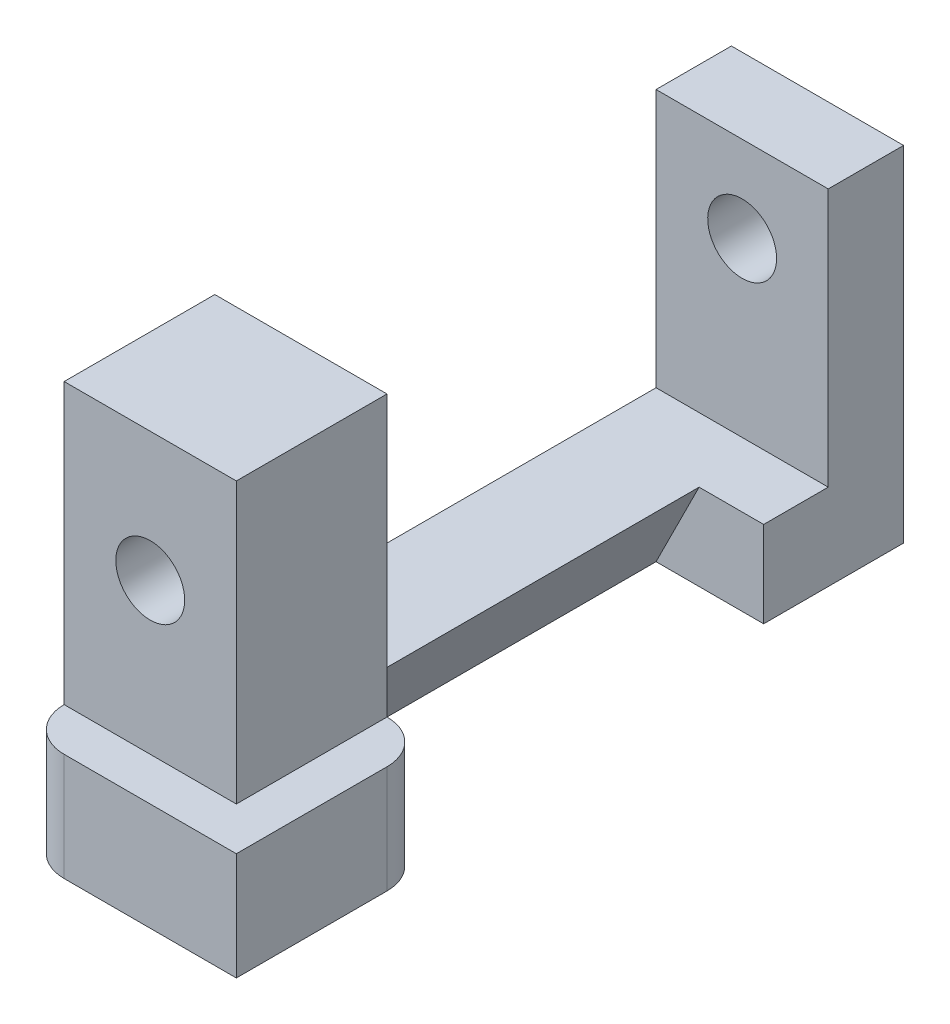
SolidWorks part; units mm, degrees
ref_plane "Front Plane" through (0, 0, 0) normal (0, 0, 1) x (1, 0, 0)
ref_plane "Top Plane" through (0, 0, 0) normal (0, 1, 0) x (1, 0, 0)
ref_plane "Right Plane" through (0, 0, 0) normal (1, 0, 0) x (0, 0, -1)
sketch "Sketch1" plane through (0, 0, 0) normal (1, 0, 0) x (0, 0, -1)
  line L0 (0, 0) -> (0, 16)
  line L1 (0, 16) -> (-3.5, 16)
  line L2 (-3.5, 16) -> (-3.5, 4)
  line L3 (-3.5, 4) -> (-24, 4)
  line L4 (-24, 4) -> (-24, 18)
  line L5 (-24, 18) -> (-31, 18)
  line L6 (-31, 18) -> (-31, 0)
  line L7 (-31, 0) -> (0, 0)
  dimension "D1" = 3.5
  dimension "D2" = 16
  dimension "D3" = 12
  dimension "D4" = 18
  dimension "D5" = 31
  dimension "D6" = 7
extrude "Boss-Extrude1" add sketch "Sketch1" against normal blind 8
sketch "Sketch3" plane through (-8, 0, 0) normal (-1, 0, 0) x (0, 0, 1)
  line L0 (3.5, 16) -> (3.5, 4) construction
  line L1 (3.5, 4) -> (24, 4)
  line L2 (3.5, 4) -> (3.5, 0)
  line L3 (3.5, 0) -> (24, 0)
  line L4 (24, 4) -> (24, 0)
  line L5 (24, 4) -> (24, 18) construction
  line L6 (31, 0) -> (0, 0) construction
  line L7 (3.5, 4) -> (24, 4) construction
extrude "Cut-Extrude1" [suppressed] cut sketch "Sketch3" against normal blind 4
sketch "Sketch5" plane through (0, 0, 3.5) normal (0, 0, 1) x (1, 0, 0)
  line L0 (-8, 0) -> (-3, 0)
  line L1 (-8, 0) -> (0, 0) construction
  line L2 (-3, 0) -> (-5, 4)
  line L3 (-5, 4) -> (-8, 4)
  line L4 (-8, 18) -> (-8, 0) construction
  line L5 (-8, 4) -> (-8, 0)
  dimension "D1" = 5
  dimension "D2" = 3
  dimension "D3" = 4
extrude "Cut-Extrude2" cut sketch "Sketch5" along normal up to surface (20.5 mm away) up to face at (-4, 11, 24)
mirror "Mirror1" about plane through (-8, 0, 0) normal (1, 0, 0) of "Cut-Extrude2", "Boss-Extrude1"
sketch "Sketch6" plane through (0, 0, 0) normal (1, 0, 0) x (0, 0, -1)
  line L1 (-33.8961, 19.8263) -> (1.3743, 19.8263)
  line L2 (-33.8961, 19.8263) -> (-33.8961, -2.4003)
  line L3 (-33.8961, -2.4003) -> (1.3743, -2.4003)
  line L4 (1.3743, 19.8263) -> (1.3743, -2.4003)
extrude "Cut-Extrude3" cut sketch "Sketch6" against normal blind 8
sketch "Sketch7" plane through (0, 0, 31) normal (0, 0, 1) x (1, 0, 0)
  line L0 (-16, 0) -> (-8, 0) construction
  line L1 (-8, 0) -> (-8, 18) construction
  circle A0 centre (-12, 12) radius 1.6
  point P4 (-12, 0)
  dimension "D1" = 3.2
  dimension "D2" = 12
  dimension "D3" = 4
sketch "Sketch9" plane through (0, 0, 3.5) normal (0, 0, 1) x (1, 0, 0)
  line L0 (-11, 4) -> (-13, 0)
  line L1 (-13, 0) -> (-8, 0)
  line L2 (-8, 0) -> (-8, 4)
  line L3 (-8, 0) -> (-8, 16) construction
  line L4 (-8, 4) -> (-11, 4)
extrude "Boss-Extrude2" add sketch "Sketch9" along normal blind 3
sketch "Sketch13" plane through (0, 0, 0) normal (0, -1, 0) x (1, 0, 0)
  line L0 (-14, 33) -> (-6, 33)
  line L1 (-6, 33) -> (-6, 26)
  line L2 (-16, 31) -> (-16, 0) construction
  line L3 (-16, 31) -> (-8, 31) construction
  line L4 (-8, 24) -> (-13, 24) construction
  line L5 (-8, 24) -> (-8, 31) construction
  line L6 (-16, 31) -> (-8, 31)
  line L7 (-8, 31) -> (-8, 24)
  arc A0 (-6, 26) -> (-8, 24) centre (-8, 26) cw
  arc A1 (-14, 33) -> (-16, 31) centre (-14, 31) ccw
  dimension "D1" = 2
  dimension "D2" = 2
extrude "Boss-Extrude7" add sketch "Sketch13" against normal blind 5
extrude "Cut-Extrude6" cut sketch "Sketch7" against normal through all
